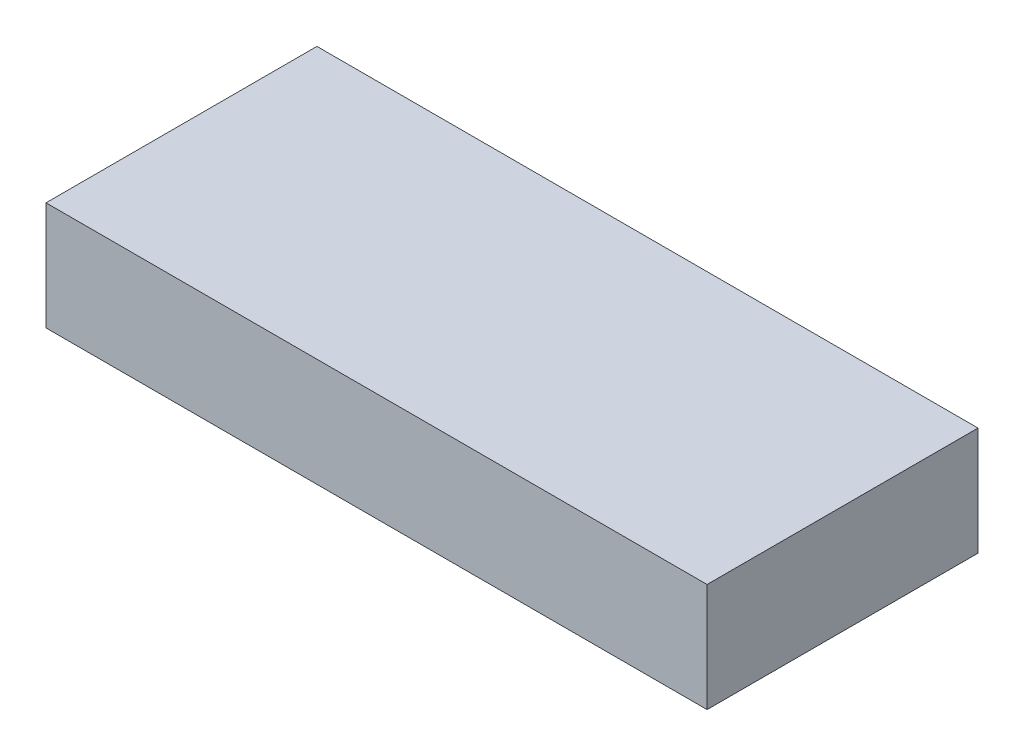
SolidWorks part; units mm, degrees
ref_plane "Front Plane" through (0, 0, 0) normal (0, 0, 1) x (1, 0, 0)
ref_plane "Top Plane" through (0, 0, 0) normal (0, 1, 0) x (1, 0, 0)
ref_plane "Right Plane" through (0, 0, 0) normal (1, 0, 0) x (0, 0, -1)
sketch "Sketch1" plane through (0, 0, 0) normal (0, 1, 0) x (1, 0, 0)
  line L1 (-30.5, -12.5) -> (30.5, -12.5)
  line L2 (-30.5, -12.5) -> (-30.5, 12.5)
  line L3 (-30.5, 12.5) -> (30.5, 12.5)
  line L4 (30.5, -12.5) -> (30.5, 12.5)
  line L5 (-30.5, -12.5) -> (30.5, 12.5) construction
  line L6 (-30.5, 12.5) -> (30.5, -12.5) construction
  point P0 (0, 0)
  dimension "D1" = 25
  dimension "D2" = 61
extrude "Boss-Extrude1" add sketch "Sketch1" along normal blind 10
